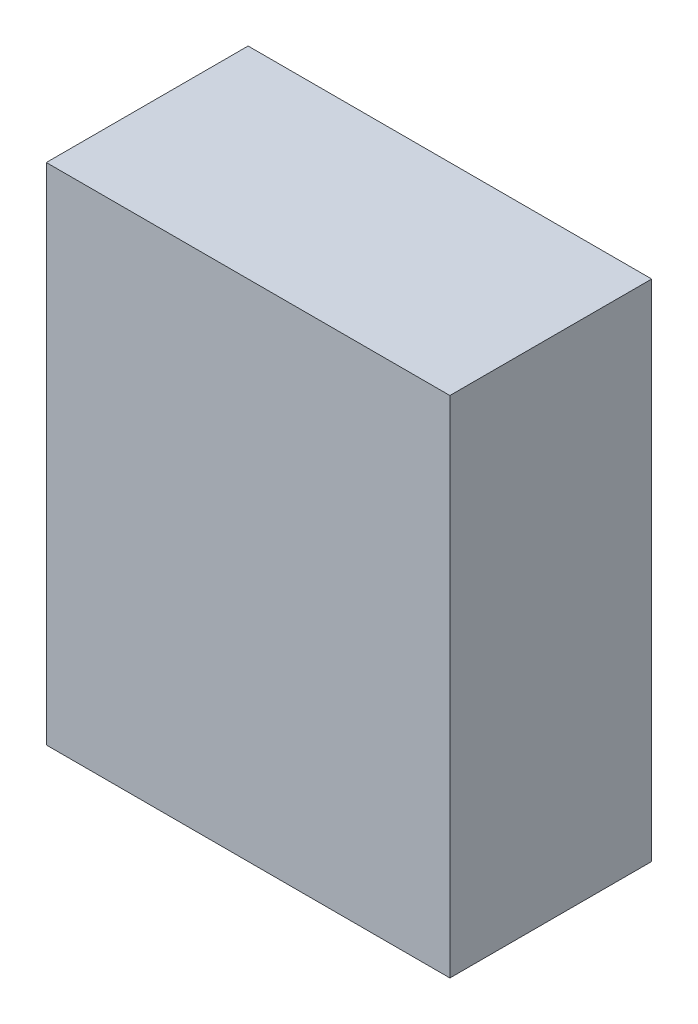
SolidWorks part; units mm, degrees
ref_plane "Front Plane" through (0, 0, 0) normal (0, 0, 1) x (1, 0, 0)
ref_plane "Top Plane" through (0, 0, 0) normal (0, 1, 0) x (1, 0, 0)
ref_plane "Right Plane" through (0, 0, 0) normal (1, 0, 0) x (0, 0, -1)
sketch "Sketch1" plane through (0, 0, 0) normal (0, 0, 1) x (1, 0, 0)
  line L1 (-400, -500) -> (400, -500)
  line L2 (-400, -500) -> (-400, 500)
  line L3 (-400, 500) -> (400, 500)
  line L4 (400, -500) -> (400, 500)
  line L5 (-400, -500) -> (400, 500) construction
  line L6 (-400, 500) -> (400, -500) construction
  point P0 (0, 0)
  dimension "D1" = 1000
  dimension "D2" = 800
extrude "Boss-Extrude1" add sketch "Sketch1" along normal blind 400
